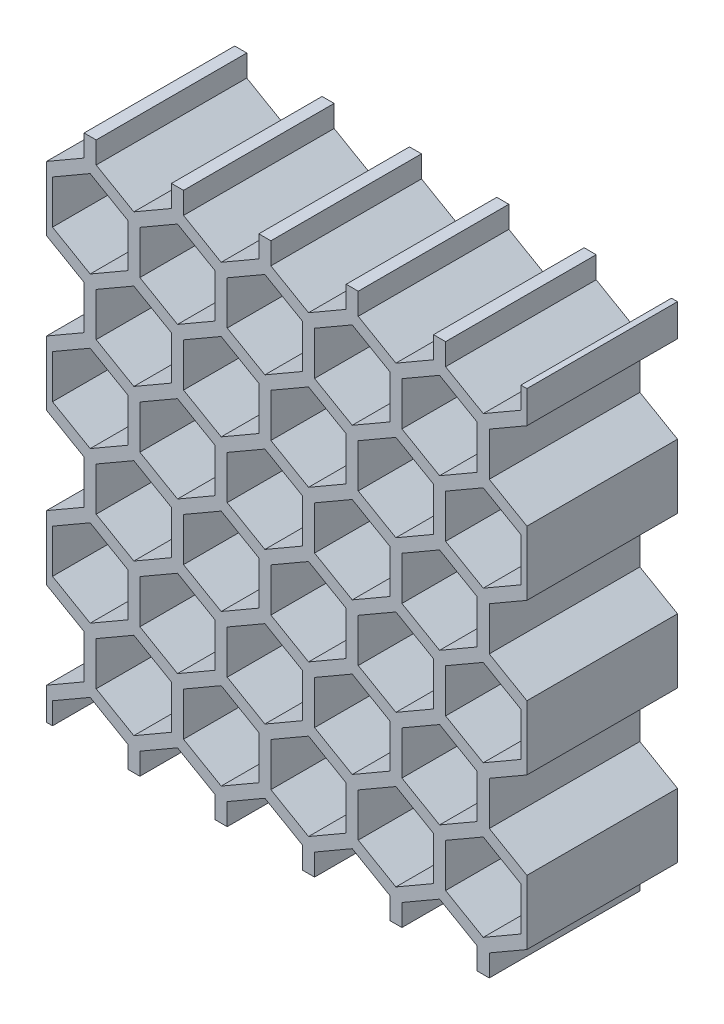
SolidWorks part; units mm, degrees
ref_plane "Front Plane" through (0, 0, 0) normal (0, 0, 1) x (1, 0, 0)
ref_plane "Top Plane" through (0, 0, 0) normal (0, 1, 0) x (1, 0, 0)
ref_plane "Right Plane" through (0, 0, 0) normal (1, 0, 0) x (0, 0, -1)
sketch "Sketch1" plane through (0, 0, 0) normal (0, 0, 1) x (1, 0, 0)
  line L0 (8.3, -1.4434) -> (8.3, 1.4434)
  line L1 (2.5, -1.4434) -> (2.5, 1.4434)
  line L2 (2.5, 1.4434) -> (0, 2.8868)
  line L3 (0, 2.8868) -> (-2.5, 1.4434)
  line L4 (-2.5, 1.4434) -> (-2.5, -1.4434)
  line L5 (-2.5, -1.4434) -> (0, -2.8868)
  line L6 (0, -2.8868) -> (2.5, -1.4434)
  line L7 (5.4, -6.4663) -> (5.4, -3.5796)
  line L8 (5.4, -3.5796) -> (2.9, -2.1362)
  line L9 (2.9, -2.1362) -> (0.4, -3.5796)
  line L10 (0.4, -3.5796) -> (0.4, -6.4663)
  line L11 (0.4, -6.4663) -> (2.9, -7.9097)
  line L12 (2.9, -7.9097) -> (5.4, -6.4663)
  line L13 (8.3, 1.4434) -> (5.8, 2.8868)
  line L14 (5.8, 2.8868) -> (3.3, 1.4434)
  line L15 (3.3, 1.4434) -> (3.3, -1.4434)
  line L16 (3.3, -1.4434) -> (5.8, -2.8868)
  line L17 (5.8, -2.8868) -> (8.3, -1.4434)
  line L18 (11.2, -6.4663) -> (11.2, -3.5796)
  line L19 (11.2, -3.5796) -> (8.7, -2.1362)
  line L20 (8.7, -2.1362) -> (6.2, -3.5796)
  line L21 (6.2, -3.5796) -> (6.2, -6.4663)
  line L22 (6.2, -6.4663) -> (8.7, -7.9097)
  line L23 (8.7, -7.9097) -> (11.2, -6.4663)
  line L24 (14.1, -1.4434) -> (14.1, 1.4434)
  line L25 (14.1, 1.4434) -> (11.6, 2.8868)
  line L26 (11.6, 2.8868) -> (9.1, 1.4434)
  line L27 (9.1, 1.4434) -> (9.1, -1.4434)
  line L28 (9.1, -1.4434) -> (11.6, -2.8868)
  line L29 (11.6, -2.8868) -> (14.1, -1.4434)
  line L30 (17, -6.4663) -> (17, -3.5796)
  line L31 (17, -3.5796) -> (14.5, -2.1362)
  line L32 (14.5, -2.1362) -> (12, -3.5796)
  line L33 (12, -3.5796) -> (12, -6.4663)
  line L34 (12, -6.4663) -> (14.5, -7.9097)
  line L35 (14.5, -7.9097) -> (17, -6.4663)
  line L36 (19.9, -1.4434) -> (19.9, 1.4434)
  line L37 (19.9, 1.4434) -> (17.4, 2.8868)
  line L38 (17.4, 2.8868) -> (14.9, 1.4434)
  line L39 (14.9, 1.4434) -> (14.9, -1.4434)
  line L40 (14.9, -1.4434) -> (17.4, -2.8868)
  line L41 (17.4, -2.8868) -> (19.9, -1.4434)
  line L42 (22.8, -6.4663) -> (22.8, -3.5796)
  line L43 (22.8, -3.5796) -> (20.3, -2.1362)
  line L44 (20.3, -2.1362) -> (17.8, -3.5796)
  line L45 (17.8, -3.5796) -> (17.8, -6.4663)
  line L46 (17.8, -6.4663) -> (20.3, -7.9097)
  line L47 (20.3, -7.9097) -> (22.8, -6.4663)
  line L48 (8.3, 8.5966) -> (8.3, 11.4834)
  line L49 (8.3, 11.4834) -> (5.8, 12.9268)
  line L50 (5.8, 12.9268) -> (3.3, 11.4834)
  line L51 (3.3, 11.4834) -> (3.3, 8.5966)
  line L52 (3.3, 8.5966) -> (5.8, 7.1532)
  line L53 (5.8, 7.1532) -> (8.3, 8.5966)
  line L54 (11.2, 3.5737) -> (11.2, 6.4604)
  line L55 (11.2, 6.4604) -> (8.7, 7.9038)
  line L56 (8.7, 7.9038) -> (6.2, 6.4604)
  line L57 (6.2, 6.4604) -> (6.2, 3.5737)
  line L58 (6.2, 3.5737) -> (8.7, 2.1303)
  line L59 (8.7, 2.1303) -> (11.2, 3.5737)
  line L60 (14.1, 8.5966) -> (14.1, 11.4834)
  line L61 (14.1, 11.4834) -> (11.6, 12.9268)
  line L62 (11.6, 12.9268) -> (9.1, 11.4834)
  line L63 (9.1, 11.4834) -> (9.1, 8.5966)
  line L64 (9.1, 8.5966) -> (11.6, 7.1532)
  line L65 (11.6, 7.1532) -> (14.1, 8.5966)
  line L66 (17, 3.5737) -> (17, 6.4604)
  line L67 (17, 6.4604) -> (14.5, 7.9038)
  line L68 (14.5, 7.9038) -> (12, 6.4604)
  line L69 (12, 6.4604) -> (12, 3.5737)
  line L70 (12, 3.5737) -> (14.5, 2.1303)
  line L71 (14.5, 2.1303) -> (17, 3.5737)
  line L72 (19.9, 8.5966) -> (19.9, 11.4834)
  line L73 (19.9, 11.4834) -> (17.4, 12.9268)
  line L74 (17.4, 12.9268) -> (14.9, 11.4834)
  line L75 (14.9, 11.4834) -> (14.9, 8.5966)
  line L76 (14.9, 8.5966) -> (17.4, 7.1532)
  line L77 (17.4, 7.1532) -> (19.9, 8.5966)
  line L78 (22.8, 3.5737) -> (22.8, 6.4604)
  line L79 (22.8, 6.4604) -> (20.3, 7.9038)
  line L80 (20.3, 7.9038) -> (17.8, 6.4604)
  line L81 (17.8, 6.4604) -> (17.8, 3.5737)
  line L82 (17.8, 3.5737) -> (20.3, 2.1303)
  line L83 (20.3, 2.1303) -> (22.8, 3.5737)
  line L84 (8.3, 18.6366) -> (8.3, 21.5234)
  line L85 (8.3, 21.5234) -> (5.8, 22.9668)
  line L86 (5.8, 22.9668) -> (3.3, 21.5234)
  line L87 (3.3, 21.5234) -> (3.3, 18.6366)
  line L88 (3.3, 18.6366) -> (5.8, 17.1932)
  line L89 (5.8, 17.1932) -> (8.3, 18.6366)
  line L90 (11.2, 13.6137) -> (11.2, 16.5004)
  line L91 (11.2, 16.5004) -> (8.7, 17.9438)
  line L92 (8.7, 17.9438) -> (6.2, 16.5004)
  line L93 (6.2, 16.5004) -> (6.2, 13.6137)
  line L94 (6.2, 13.6137) -> (8.7, 12.1703)
  line L95 (8.7, 12.1703) -> (11.2, 13.6137)
  line L96 (14.1, 18.6366) -> (14.1, 21.5234)
  line L97 (14.1, 21.5234) -> (11.6, 22.9668)
  line L98 (11.6, 22.9668) -> (9.1, 21.5234)
  line L99 (9.1, 21.5234) -> (9.1, 18.6366)
  line L100 (9.1, 18.6366) -> (11.6, 17.1932)
  line L101 (11.6, 17.1932) -> (14.1, 18.6366)
  line L102 (17, 13.6137) -> (17, 16.5004)
  line L103 (17, 16.5004) -> (14.5, 17.9438)
  line L104 (14.5, 17.9438) -> (12, 16.5004)
  line L105 (12, 16.5004) -> (12, 13.6137)
  line L106 (12, 13.6137) -> (14.5, 12.1703)
  line L107 (14.5, 12.1703) -> (17, 13.6137)
  line L108 (19.9, 18.6366) -> (19.9, 21.5234)
  line L109 (19.9, 21.5234) -> (17.4, 22.9668)
  line L110 (17.4, 22.9668) -> (14.9, 21.5234)
  line L111 (14.9, 21.5234) -> (14.9, 18.6366)
  line L112 (14.9, 18.6366) -> (17.4, 17.1932)
  line L113 (17.4, 17.1932) -> (19.9, 18.6366)
  line L114 (22.8, 13.6137) -> (22.8, 16.5004)
  line L115 (22.8, 16.5004) -> (20.3, 17.9438)
  line L116 (20.3, 17.9438) -> (17.8, 16.5004)
  line L117 (17.8, 16.5004) -> (17.8, 13.6137)
  line L118 (17.8, 13.6137) -> (20.3, 12.1703)
  line L119 (20.3, 12.1703) -> (22.8, 13.6137)
  line L120 (8.3, 28.6766) -> (8.3, 31.5634)
  line L121 (8.3, 31.5634) -> (5.8, 33.0068)
  line L122 (5.8, 33.0068) -> (3.3, 31.5634)
  line L123 (3.3, 31.5634) -> (3.3, 28.6766)
  line L124 (3.3, 28.6766) -> (5.8, 27.2332)
  line L125 (5.8, 27.2332) -> (8.3, 28.6766)
  line L126 (11.2, 23.6537) -> (11.2, 26.5404)
  line L127 (11.2, 26.5404) -> (8.7, 27.9838)
  line L128 (8.7, 27.9838) -> (6.2, 26.5404)
  line L129 (6.2, 26.5404) -> (6.2, 23.6537)
  line L130 (6.2, 23.6537) -> (8.7, 22.2103)
  line L131 (8.7, 22.2103) -> (11.2, 23.6537)
  line L132 (14.1, 28.6766) -> (14.1, 31.5634)
  line L133 (14.1, 31.5634) -> (11.6, 33.0068)
  line L134 (11.6, 33.0068) -> (9.1, 31.5634)
  line L135 (9.1, 31.5634) -> (9.1, 28.6766)
  line L136 (9.1, 28.6766) -> (11.6, 27.2332)
  line L137 (11.6, 27.2332) -> (14.1, 28.6766)
  line L138 (17, 23.6537) -> (17, 26.5404)
  line L139 (17, 26.5404) -> (14.5, 27.9838)
  line L140 (14.5, 27.9838) -> (12, 26.5404)
  line L141 (12, 26.5404) -> (12, 23.6537)
  line L142 (12, 23.6537) -> (14.5, 22.2103)
  line L143 (14.5, 22.2103) -> (17, 23.6537)
  line L144 (19.9, 28.6766) -> (19.9, 31.5634)
  line L145 (19.9, 31.5634) -> (17.4, 33.0068)
  line L146 (17.4, 33.0068) -> (14.9, 31.5634)
  line L147 (14.9, 31.5634) -> (14.9, 28.6766)
  line L148 (14.9, 28.6766) -> (17.4, 27.2332)
  line L149 (17.4, 27.2332) -> (19.9, 28.6766)
  line L150 (22.8, 23.6537) -> (22.8, 26.5404)
  line L151 (22.8, 26.5404) -> (20.3, 27.9838)
  line L152 (20.3, 27.9838) -> (17.8, 26.5404)
  line L153 (17.8, 26.5404) -> (17.8, 23.6537)
  line L154 (17.8, 23.6537) -> (20.3, 22.2103)
  line L155 (20.3, 22.2103) -> (22.8, 23.6537)
  line L157 (0, 30.12) -> (31.9, 30.12)
  line L158 (0, 30.12) -> (0, -5.0229)
  line L159 (0, -5.0229) -> (31.9, -5.0229)
  line L160 (31.9, 30.12) -> (31.9, -5.0229)
  line L372 (2.5, 8.5966) -> (2.5, 11.4834)
  line L373 (2.5, 11.4834) -> (0, 12.9268)
  line L374 (0, 12.9268) -> (-2.5, 11.4834)
  line L375 (-2.5, 11.4834) -> (-2.5, 8.5966)
  line L376 (-2.5, 8.5966) -> (0, 7.1532)
  line L377 (0, 7.1532) -> (2.5, 8.5966)
  line L378 (5.4, 3.5737) -> (5.4, 6.4604)
  line L379 (5.4, 6.4604) -> (2.9, 7.9038)
  line L380 (2.9, 7.9038) -> (0.4, 6.4604)
  line L381 (0.4, 6.4604) -> (0.4, 3.5737)
  line L382 (0.4, 3.5737) -> (2.9, 2.1303)
  line L383 (2.9, 2.1303) -> (5.4, 3.5737)
  line L384 (2.5, 18.6366) -> (2.5, 21.5234)
  line L385 (2.5, 21.5234) -> (0, 22.9668)
  line L386 (0, 22.9668) -> (-2.5, 21.5234)
  line L387 (-2.5, 21.5234) -> (-2.5, 18.6366)
  line L388 (-2.5, 18.6366) -> (0, 17.1932)
  line L389 (0, 17.1932) -> (2.5, 18.6366)
  line L390 (5.4, 13.6137) -> (5.4, 16.5004)
  line L391 (5.4, 16.5004) -> (2.9, 17.9438)
  line L392 (2.9, 17.9438) -> (0.4, 16.5004)
  line L393 (0.4, 16.5004) -> (0.4, 13.6137)
  line L394 (0.4, 13.6137) -> (2.9, 12.1703)
  line L395 (2.9, 12.1703) -> (5.4, 13.6137)
  line L396 (2.5, 28.6766) -> (2.5, 31.5634)
  line L397 (2.5, 31.5634) -> (0, 33.0068)
  line L398 (0, 33.0068) -> (-2.5, 31.5634)
  line L399 (-2.5, 31.5634) -> (-2.5, 28.6766)
  line L400 (-2.5, 28.6766) -> (0, 27.2332)
  line L401 (0, 27.2332) -> (2.5, 28.6766)
  line L402 (5.4, 23.6537) -> (5.4, 26.5404)
  line L403 (5.4, 26.5404) -> (2.9, 27.9838)
  line L404 (2.9, 27.9838) -> (0.4, 26.5404)
  line L405 (0.4, 26.5404) -> (0.4, 23.6537)
  line L406 (0.4, 23.6537) -> (2.9, 22.2103)
  line L407 (2.9, 22.2103) -> (5.4, 23.6537)
  line L480 (25.7, -1.4434) -> (25.7, 1.4434)
  line L485 (25.7, 1.4434) -> (23.2, 2.8868)
  line L486 (23.2, 2.8868) -> (20.7, 1.4434)
  line L487 (20.7, 1.4434) -> (20.7, -1.4434)
  line L488 (20.7, -1.4434) -> (23.2, -2.8868)
  line L489 (23.2, -2.8868) -> (25.7, -1.4434)
  line L490 (28.6, -6.4663) -> (28.6, -3.5796)
  line L491 (28.6, -3.5796) -> (26.1, -2.1362)
  line L492 (26.1, -2.1362) -> (23.6, -3.5796)
  line L493 (23.6, -3.5796) -> (23.6, -6.4663)
  line L494 (23.6, -6.4663) -> (26.1, -7.9097)
  line L495 (26.1, -7.9097) -> (28.6, -6.4663)
  line L496 (31.5, -1.4434) -> (31.5, 1.4434)
  line L497 (31.5, 1.4434) -> (29, 2.8868)
  line L498 (29, 2.8868) -> (26.5, 1.4434)
  line L499 (26.5, 1.4434) -> (26.5, -1.4434)
  line L500 (26.5, -1.4434) -> (29, -2.8868)
  line L501 (29, -2.8868) -> (31.5, -1.4434)
  line L502 (34.4, -6.4663) -> (34.4, -3.5796)
  line L503 (34.4, -3.5796) -> (31.9, -2.1362)
  line L504 (31.9, -2.1362) -> (29.4, -3.5796)
  line L505 (29.4, -3.5796) -> (29.4, -6.4663)
  line L506 (29.4, -6.4663) -> (31.9, -7.9097)
  line L507 (31.9, -7.9097) -> (34.4, -6.4663)
  line L508 (25.7, 8.5966) -> (25.7, 11.4834)
  line L509 (25.7, 11.4834) -> (23.2, 12.9268)
  line L510 (23.2, 12.9268) -> (20.7, 11.4834)
  line L511 (20.7, 11.4834) -> (20.7, 8.5966)
  line L512 (20.7, 8.5966) -> (23.2, 7.1532)
  line L513 (23.2, 7.1532) -> (25.7, 8.5966)
  line L514 (28.6, 3.5737) -> (28.6, 6.4604)
  line L515 (28.6, 6.4604) -> (26.1, 7.9038)
  line L516 (26.1, 7.9038) -> (23.6, 6.4604)
  line L517 (23.6, 6.4604) -> (23.6, 3.5737)
  line L518 (23.6, 3.5737) -> (26.1, 2.1303)
  line L519 (26.1, 2.1303) -> (28.6, 3.5737)
  line L520 (31.5, 8.5966) -> (31.5, 11.4834)
  line L521 (31.5, 11.4834) -> (29, 12.9268)
  line L522 (29, 12.9268) -> (26.5, 11.4834)
  line L523 (26.5, 11.4834) -> (26.5, 8.5966)
  line L524 (26.5, 8.5966) -> (29, 7.1532)
  line L525 (29, 7.1532) -> (31.5, 8.5966)
  line L526 (34.4, 3.5737) -> (34.4, 6.4604)
  line L527 (34.4, 6.4604) -> (31.9, 7.9038)
  line L528 (31.9, 7.9038) -> (29.4, 6.4604)
  line L529 (29.4, 6.4604) -> (29.4, 3.5737)
  line L530 (29.4, 3.5737) -> (31.9, 2.1303)
  line L531 (31.9, 2.1303) -> (34.4, 3.5737)
  line L532 (25.7, 18.6366) -> (25.7, 21.5234)
  line L533 (25.7, 21.5234) -> (23.2, 22.9668)
  line L534 (23.2, 22.9668) -> (20.7, 21.5234)
  line L535 (20.7, 21.5234) -> (20.7, 18.6366)
  line L536 (20.7, 18.6366) -> (23.2, 17.1932)
  line L537 (23.2, 17.1932) -> (25.7, 18.6366)
  line L538 (28.6, 13.6137) -> (28.6, 16.5004)
  line L539 (28.6, 16.5004) -> (26.1, 17.9438)
  line L540 (26.1, 17.9438) -> (23.6, 16.5004)
  line L541 (23.6, 16.5004) -> (23.6, 13.6137)
  line L542 (23.6, 13.6137) -> (26.1, 12.1703)
  line L543 (26.1, 12.1703) -> (28.6, 13.6137)
  line L544 (31.5, 18.6366) -> (31.5, 21.5234)
  line L545 (31.5, 21.5234) -> (29, 22.9668)
  line L546 (29, 22.9668) -> (26.5, 21.5234)
  line L547 (26.5, 21.5234) -> (26.5, 18.6366)
  line L548 (26.5, 18.6366) -> (29, 17.1932)
  line L549 (29, 17.1932) -> (31.5, 18.6366)
  line L550 (34.4, 13.6137) -> (34.4, 16.5004)
  line L551 (34.4, 16.5004) -> (31.9, 17.9438)
  line L552 (31.9, 17.9438) -> (29.4, 16.5004)
  line L553 (29.4, 16.5004) -> (29.4, 13.6137)
  line L554 (29.4, 13.6137) -> (31.9, 12.1703)
  line L555 (31.9, 12.1703) -> (34.4, 13.6137)
  line L556 (25.7, 28.6766) -> (25.7, 31.5634)
  line L557 (25.7, 31.5634) -> (23.2, 33.0068)
  line L558 (23.2, 33.0068) -> (20.7, 31.5634)
  line L559 (20.7, 31.5634) -> (20.7, 28.6766)
  line L560 (20.7, 28.6766) -> (23.2, 27.2332)
  line L561 (23.2, 27.2332) -> (25.7, 28.6766)
  line L562 (28.6, 23.6537) -> (28.6, 26.5404)
  line L563 (28.6, 26.5404) -> (26.1, 27.9838)
  line L564 (26.1, 27.9838) -> (23.6, 26.5404)
  line L565 (23.6, 26.5404) -> (23.6, 23.6537)
  line L566 (23.6, 23.6537) -> (26.1, 22.2103)
  line L567 (26.1, 22.2103) -> (28.6, 23.6537)
  line L568 (31.5, 28.6766) -> (31.5, 31.5634)
  line L569 (31.5, 31.5634) -> (29, 33.0068)
  line L570 (29, 33.0068) -> (26.5, 31.5634)
  line L571 (26.5, 31.5634) -> (26.5, 28.6766)
  line L572 (26.5, 28.6766) -> (29, 27.2332)
  line L573 (29, 27.2332) -> (31.5, 28.6766)
  line L574 (34.4, 23.6537) -> (34.4, 26.5404)
  line L575 (34.4, 26.5404) -> (31.9, 27.9838)
  line L576 (31.9, 27.9838) -> (29.4, 26.5404)
  line L577 (29.4, 26.5404) -> (29.4, 23.6537)
  line L578 (29.4, 23.6537) -> (31.9, 22.2103)
  line L579 (31.9, 22.2103) -> (34.4, 23.6537)
  circle A0 centre (0, 0) radius 2.5 construction
  circle A1 centre (2.9, -5.0229) radius 2.5 construction
  circle A2 centre (5.8, 0) radius 2.5 construction
  circle A3 centre (8.7, -5.0229) radius 2.5 construction
  circle A4 centre (11.6, 0) radius 2.5 construction
  circle A5 centre (14.5, -5.0229) radius 2.5 construction
  circle A6 centre (17.4, 0) radius 2.5 construction
  circle A7 centre (20.3, -5.0229) radius 2.5 construction
  circle A8 centre (5.8, 10.04) radius 2.5 construction
  circle A9 centre (8.7, 5.0171) radius 2.5 construction
  circle A10 centre (11.6, 10.04) radius 2.5 construction
  circle A11 centre (14.5, 5.0171) radius 2.5 construction
  circle A12 centre (17.4, 10.04) radius 2.5 construction
  circle A13 centre (20.3, 5.0171) radius 2.5 construction
  circle A14 centre (5.8, 20.08) radius 2.5 construction
  circle A15 centre (8.7, 15.0571) radius 2.5 construction
  circle A16 centre (11.6, 20.08) radius 2.5 construction
  circle A17 centre (14.5, 15.0571) radius 2.5 construction
  circle A18 centre (17.4, 20.08) radius 2.5 construction
  circle A19 centre (20.3, 15.0571) radius 2.5 construction
  circle A20 centre (5.8, 30.12) radius 2.5 construction
  circle A21 centre (8.7, 25.0971) radius 2.5 construction
  circle A22 centre (11.6, 30.12) radius 2.5 construction
  circle A23 centre (14.5, 25.0971) radius 2.5 construction
  circle A24 centre (17.4, 30.12) radius 2.5 construction
  circle A25 centre (20.3, 25.0971) radius 2.5 construction
  circle A62 centre (0, 10.04) radius 2.5 construction
  circle A63 centre (2.9, 5.0171) radius 2.5 construction
  circle A64 centre (0, 20.08) radius 2.5 construction
  circle A65 centre (2.9, 15.0571) radius 2.5 construction
  circle A66 centre (0, 30.12) radius 2.5 construction
  circle A67 centre (2.9, 25.0971) radius 2.5 construction
  circle A80 centre (23.2, 0) radius 2.5 construction
  circle A81 centre (26.1, -5.0229) radius 2.5 construction
  circle A82 centre (29, 0) radius 2.5 construction
  circle A83 centre (31.9, -5.0229) radius 2.5 construction
  circle A84 centre (23.2, 10.04) radius 2.5 construction
  circle A85 centre (26.1, 5.0171) radius 2.5 construction
  circle A86 centre (29, 10.04) radius 2.5 construction
  circle A87 centre (31.9, 5.0171) radius 2.5 construction
  circle A88 centre (23.2, 20.08) radius 2.5 construction
  circle A89 centre (26.1, 15.0571) radius 2.5 construction
  circle A90 centre (29, 20.08) radius 2.5 construction
  circle A91 centre (31.9, 15.0571) radius 2.5 construction
  circle A92 centre (23.2, 30.12) radius 2.5 construction
  circle A93 centre (26.1, 25.0971) radius 2.5 construction
  circle A94 centre (29, 30.12) radius 2.5 construction
  circle A95 centre (31.9, 25.0971) radius 2.5 construction
  dimension "D1" = 5
  dimension "D2" = 5
  dimension "D3" = 0.8
  dimension "D4" = 0.4
  dimension "D5" = 5.4
  dimension "D6" = 9.3531
  dimension "D7" = 0.6928
  dimension "D8" = 0.4
  dimension "D9" = 6
  dimension "D10" = 4
extrude "Boss-Extrude1" add sketch "Sketch1" along normal blind 10
